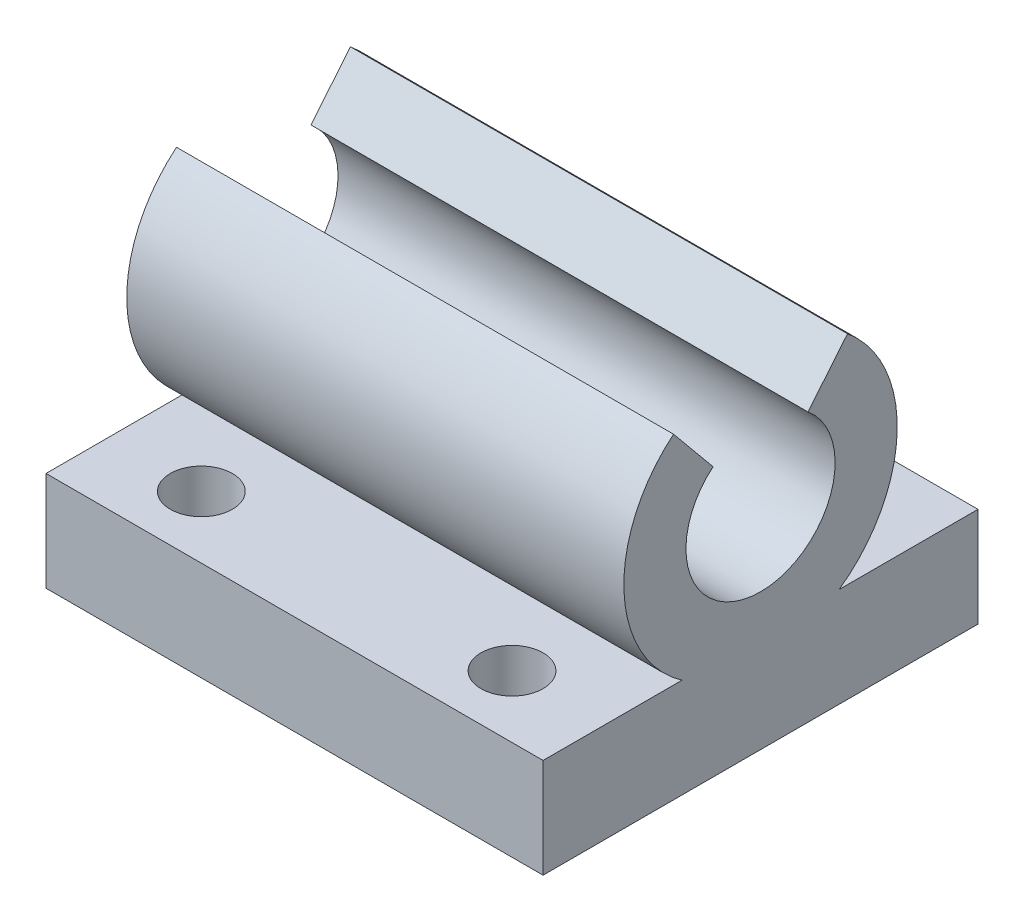
SolidWorks part; units mm, degrees
ref_plane "Спереди" through (0, 0, 0) normal (0, 0, 1) x (1, 0, 0)
ref_plane "Сверху" through (0, 0, 0) normal (0, 1, 0) x (1, 0, 0)
ref_plane "Справа" through (0, 0, 0) normal (1, 0, 0) x (0, 0, -1)
sketch "Эскиз1" plane through (0, 0, 0) normal (1, 0, 0) x (0, 0, -1)
  line L0 (0, 0) -> (0, -4.1776) construction
  line L1 (-17.5, 8) -> (17.5, 8)
  line L2 (-17.5, 8) -> (-17.5, 0)
  line L3 (-17.5, 0) -> (17.5, 0)
  line L4 (17.5, 8) -> (17.5, 0)
  line L5 (0, 17) -> (-7, 25.4853)
  line L6 (0, 17) -> (7, 25.4853)
  circle A0 centre (0, 17) radius 6
  circle A1 centre (0, 17) radius 11
  dimension "D3" = 12
  dimension "D5" = 28
  dimension "D1" = 35
  dimension "D2" = 8
  dimension "D6" = 14
  dimension "D4" = 5
sketch "Эскиз2" plane through (0, 0, 0) normal (1, 0, 0) x (0, 0, -1)
  line L0 (0, 17) -> (-7, 25.4853) construction
  line L1 (0, 17) -> (7, 25.4853) construction
  line L2 (-3.8182, 21.6283) -> (-7, 25.4853)
  line L3 (3.8182, 21.6283) -> (7, 25.4853)
  line L4 (17.5, 8) -> (-17.5, 8)
  line L5 (17.5, 0) -> (17.5, 8)
  line L6 (-17.5, 0) -> (17.5, 0)
  line L7 (-17.5, 8) -> (-17.5, 0)
  line L8 (17.5, 8) -> (6.3246, 8)
  line L9 (17.5, 0) -> (17.5, 8)
  line L10 (-17.5, 0) -> (17.5, 0)
  line L11 (-17.5, 8) -> (-17.5, 0)
  line L12 (-6.3246, 8) -> (-17.5, 8)
  arc A0 (6.3246, 8) -> (7, 25.4853) centre (0, 17) ccw
  circle A1 centre (0, 17) radius 11
  arc A2 (-7, 25.4853) -> (-6.3246, 8) centre (0, 17) ccw
  circle A3 centre (0, 17) radius 6
  arc A4 (-3.8182, 21.6283) -> (3.8182, 21.6283) centre (0, 17) ccw
  dimension "D1" = 0
  dimension "D2" = 0
  dimension "D3" = 0
extrude "Бобышка-Вытянуть1" add sketch "Эскиз2" along normal mid plane 40
sketch "Эскиз3" plane through (0, 0, 0) normal (0, -1, 0) x (1, 0, 0)
  line L0 (0, 5.1194) -> (0, 0) construction
  line L1 (0, 0) -> (3.3596, 0) construction
  circle A0 centre (-12.5, 12.5) radius 2.5
  circle A1 centre (12.5, 12.5) radius 2.5
  circle A2 centre (-12.5, -12.5) radius 2.5
  circle A3 centre (12.5, -12.5) radius 2.5
  dimension "D1" = 5
  dimension "D2" = 25
  dimension "D3" = 25
extrude "Вырез-Вытянуть1" cut sketch "Эскиз3" against normal up to next
